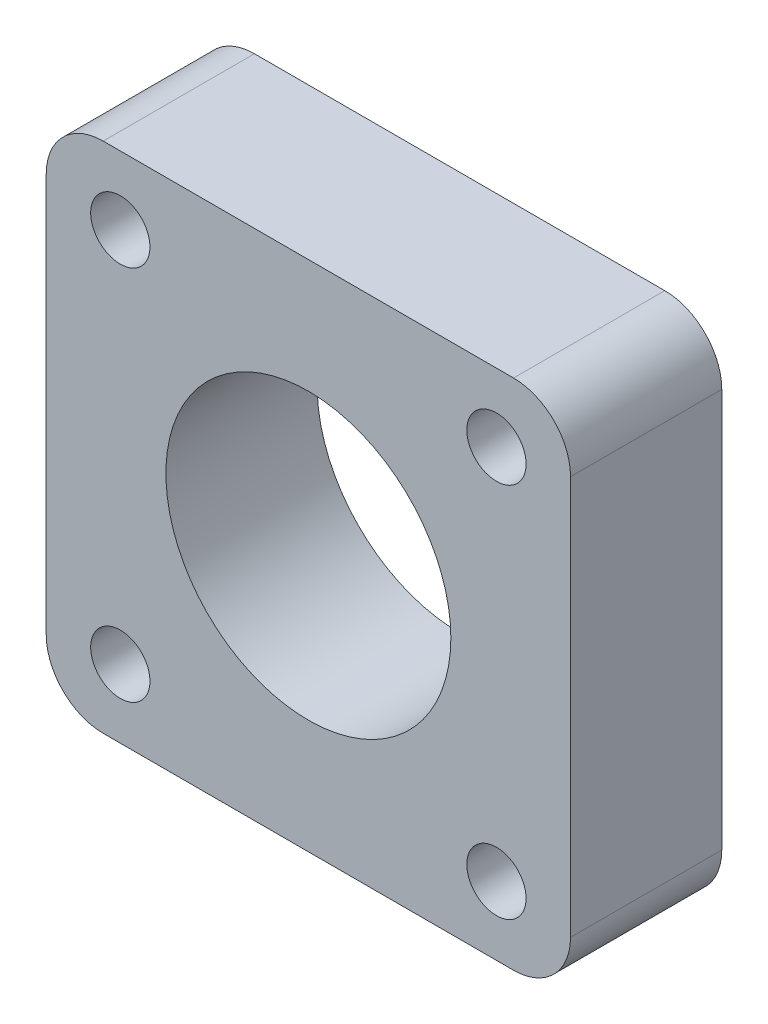
SolidWorks part; units mm, degrees
ref_plane "Спереди" through (0, 0, 0) normal (0, 0, 1) x (1, 0, 0)
ref_plane "Сверху" through (0, 0, 0) normal (0, 1, 0) x (1, 0, 0)
ref_plane "Справа" through (0, 0, 0) normal (1, 0, 0) x (0, 0, -1)
sketch "Эскиз1" plane through (0, 0, 36.7311) normal (0, 0, 1) x (1, 0, 0)
  line L4 (114.0853, 309.6759) -> (114.0853, 274.6759)
  line L5 (119.0853, 269.6759) -> (155.0853, 269.6759)
  line L6 (160.0853, 274.6759) -> (160.0853, 309.6759)
  line L7 (155.0853, 314.6759) -> (119.0853, 314.6759)
  line L8 (114.0853, 309.6759) -> (114.0853, 274.6759)
  line L9 (119.0853, 269.6759) -> (155.0853, 269.6759)
  line L10 (160.0853, 274.6759) -> (160.0853, 309.6759)
  line L11 (155.0853, 314.6759) -> (119.0853, 314.6759)
  arc A4 (114.0853, 274.6759) -> (119.0853, 269.6759) centre (119.0853, 274.6759) ccw
  arc A5 (155.0853, 269.6759) -> (160.0853, 274.6759) centre (155.0853, 274.6759) ccw
  arc A6 (160.0853, 309.6759) -> (155.0853, 314.6759) centre (155.0853, 309.6759) ccw
  arc A7 (119.0853, 314.6759) -> (114.0853, 309.6759) centre (119.0853, 309.6759) ccw
  arc A8 (114.0853, 274.6759) -> (119.0853, 269.6759) centre (119.0853, 274.6759) ccw
  arc A9 (155.0853, 269.6759) -> (160.0853, 274.6759) centre (155.0853, 274.6759) ccw
  arc A10 (160.0853, 309.6759) -> (155.0853, 314.6759) centre (155.0853, 309.6759) ccw
  arc A11 (119.0853, 314.6759) -> (114.0853, 309.6759) centre (119.0853, 309.6759) ccw
  dimension "D1" = 0
extrude "Бобышка-Вытянуть1" add sketch "Эскиз1" along normal up to surface (13.2689 mm away)
sketch "Эскиз2" plane through (0, 0, 50) normal (0, 0, 1) x (1, 0, 0)
  circle A0 centre (153.5853, 308.6759) radius 2.6 construction
  circle A1 centre (120.5853, 308.6759) radius 2.6 construction
  circle A2 centre (120.5853, 275.6759) radius 2.6 construction
  circle A3 centre (153.5853, 275.6759) radius 2.6 construction
  circle A4 centre (153.5853, 308.6759) radius 2.6
  circle A5 centre (120.5853, 308.6759) radius 2.6
  circle A6 centre (120.5853, 275.6759) radius 2.6
  circle A7 centre (153.5853, 275.6759) radius 2.6
extrude "Вырез-Вытянуть1" cut sketch "Эскиз2" against normal blind 30
sketch "Эскиз3" plane through (0, 0, 50) normal (0, 0, 1) x (1, 0, 0)
  line L0 (153.5853, 308.6759) -> (120.5853, 275.6759) construction
  circle A0 centre (137.0853, 292.1759) radius 12.5
  dimension "D1" = 25
extrude "Вырез-Вытянуть2" cut sketch "Эскиз3" against normal blind 30
